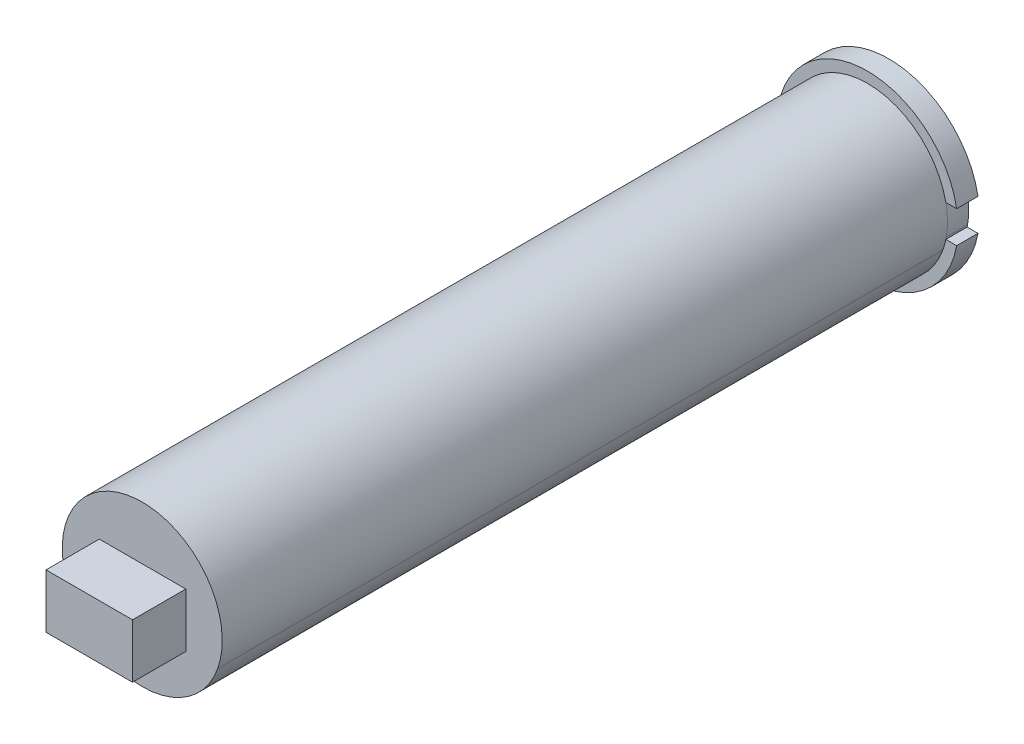
SolidWorks part; units mm, degrees
ref_plane "Front Plane" through (0, 0, 0) normal (0, 0, 1) x (1, 0, 0)
ref_plane "Top Plane" through (0, 0, 0) normal (0, 1, 0) x (1, 0, 0)
ref_plane "Right Plane" through (0, 0, 0) normal (1, 0, 0) x (0, 0, -1)
sketch "Sketch1" plane through (0, 0, 0) normal (0, 0, 1) x (1, 0, 0)
  line L0 (8.3666, 1.5) -> (7.3484, 1.5)
  line L1 (7.386, -1.3024) -> (7.3484, -1.5)
  line L2 (7.3484, -1.5) -> (8.3666, -1.5)
  line L3 (-8.3666, 1.5) -> (-7.3484, 1.5)
  line L4 (-7.3484, -1.5) -> (-8.3666, -1.5)
  arc A0 (8.3666, -1.5) -> (-8.3666, -1.5) centre (0, 0) cw
  arc A1 (8.3666, 1.5) -> (-8.3666, 1.5) centre (0, 0) ccw
  arc A2 (7.3484, 1.5) -> (7.386, -1.3024) centre (0.0009, 0) cw
  arc A3 (-7.3484, 1.5) -> (-7.3484, -1.5) centre (-0.0009, 0) ccw
extrude "Boss-Extrude1" add sketch "Sketch1" along normal blind 70
sketch "Sketch3" plane through (0, 0, 70) normal (0, 0, 1) x (1, 0, 0)
  line L10 (7.071, -2.5) -> (6.1403, -2.5)
  line L11 (6.1403, -2.5) -> (6.4024, -1.1223)
  line L12 (5.9999, 2.5) -> (7.071, 2.5)
  line L13 (-7.071, 2.5) -> (-5.9999, 2.5)
  line L14 (-5.9999, -2.5) -> (-7.071, -2.5)
  line L15 (7.071, -2.5) -> (6.1403, -2.5)
  line L16 (6.1403, -2.5) -> (6.4024, -1.1223)
  line L17 (5.9999, 2.5) -> (7.071, 2.5)
  line L18 (-7.071, 2.5) -> (-5.9999, 2.5)
  line L19 (-5.9999, -2.5) -> (-7.071, -2.5)
  arc A8 (-7.071, -2.5) -> (7.071, -2.5) centre (0, 0) ccw
  arc A9 (6.4024, -1.1223) -> (5.9999, 2.5) centre (0.0009, 0) ccw
  arc A10 (7.071, 2.5) -> (-7.071, 2.5) centre (0, 0) ccw
  arc A11 (-5.9999, 2.5) -> (-5.9999, -2.5) centre (-0.0009, 0) ccw
  arc A12 (-7.071, -2.5) -> (7.071, -2.5) centre (0, 0) ccw
  arc A13 (6.4024, -1.1223) -> (5.9999, 2.5) centre (0.0009, 0) ccw
  arc A14 (7.071, 2.5) -> (-7.071, 2.5) centre (0, 0) ccw
  arc A15 (-5.9999, 2.5) -> (-5.9999, -2.5) centre (-0.0009, 0) ccw
  dimension "D1" = 1
extrude "Cut-Extrude1" cut sketch "Sketch3" against normal blind 68 flip side to cut
sketch "Sketch4" plane through (0, 0, 70) normal (0, 0, 1) x (1, 0, 0)
  circle A0 centre (0, 0) radius 7.5
extrude "Boss-Extrude2" add sketch "Sketch4" against normal blind 68
sketch "Sketch5" plane through (0, 0, 70) normal (0, 0, 1) x (1, 0, 0)
  line L0 (-4.0261, 2.4757) -> (4.085, 2.4757)
  line L1 (-4.0261, 2.4757) -> (-4.0261, -2.5937)
  line L2 (-4.0261, -2.5937) -> (4.085, -2.5937)
  line L3 (4.085, 2.4757) -> (4.085, -2.5937)
  line L4 (-4.0261, 2.4757) -> (4.085, -2.5937) construction
  line L5 (-4.0261, -2.5937) -> (4.085, 2.4757) construction
  point P4 (0.0295, -0.059)
extrude "Boss-Extrude3" add sketch "Sketch5" along normal blind 5
